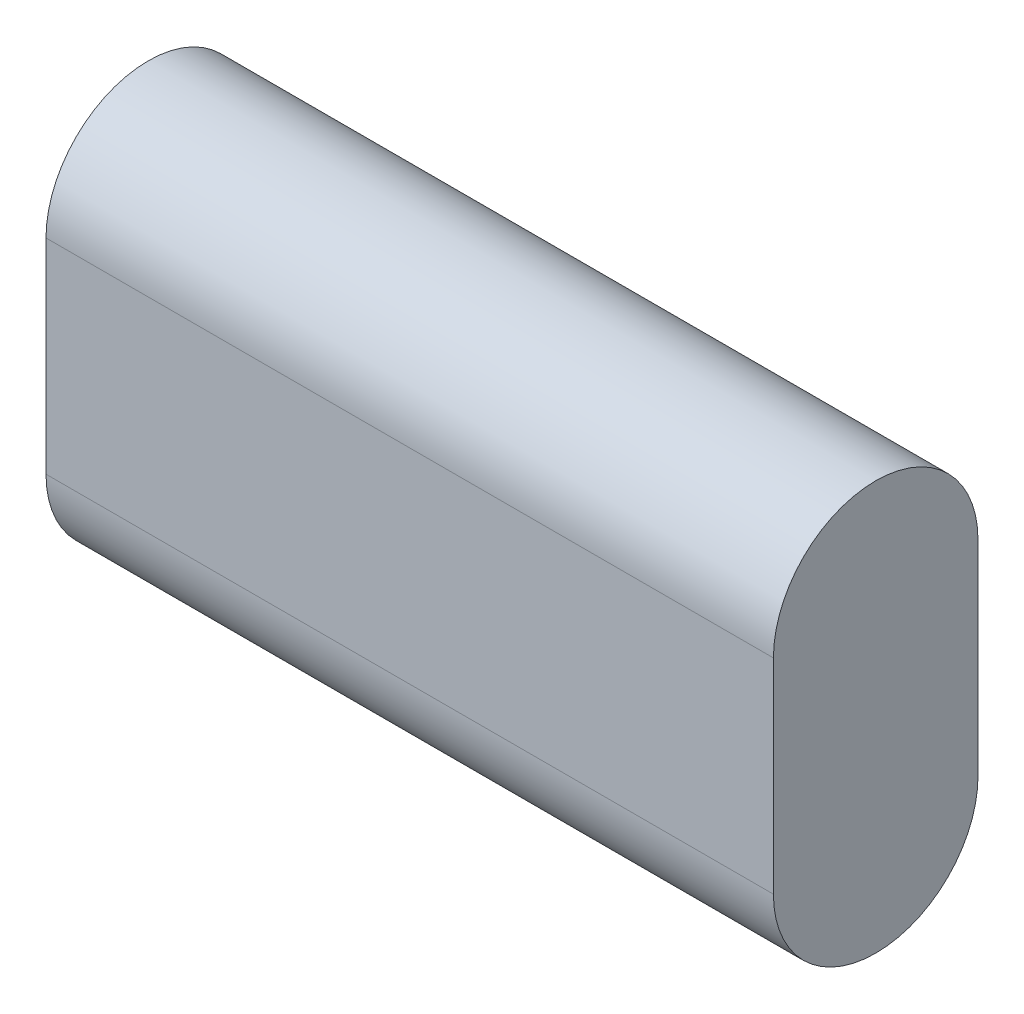
SolidWorks part; units mm, degrees
ref_plane "Front Plane" through (0, 0, 0) normal (0, 0, 1) x (1, 0, 0)
ref_plane "Top Plane" through (0, 0, 0) normal (0, 1, 0) x (1, 0, 0)
ref_plane "Right Plane" through (0, 0, 0) normal (1, 0, 0) x (0, 0, -1)
sketch "Sketch1" plane through (0, 0, 0) normal (1, 0, 0) x (0, 0, -1)
  line L0 (0, 0) -> (0, 18) construction
  line L1 (-9, 0) -> (-9, 18)
  line L2 (9, 0) -> (9, 18)
  arc A0 (-9, 0) -> (9, 0) centre (0, 0) ccw
  arc A1 (9, 18) -> (-9, 18) centre (0, 18) ccw
  point P3 (0, 9)
  dimension "D1" = 9
  dimension "D2" = 18
extrude "Boss-Extrude1" add sketch "Sketch1" along normal blind 64
